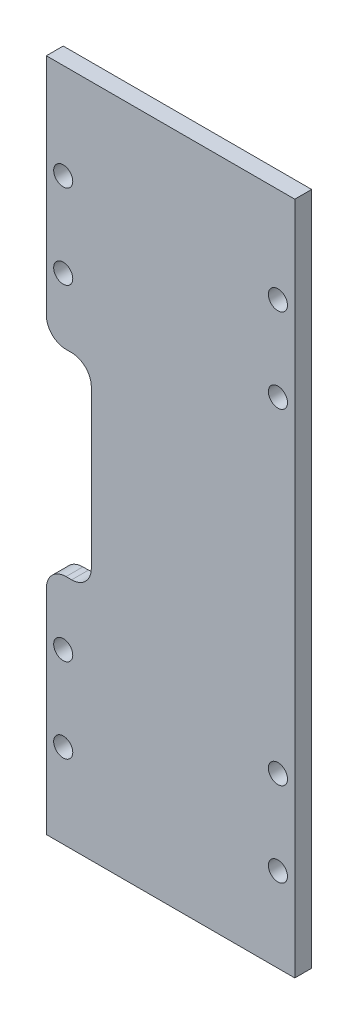
SolidWorks part; units mm, degrees
material "6061-T6 (SS)"
ref_plane "Front Plane" through (0, 0, 0) normal (0, 0, 1) x (1, 0, 0)
ref_plane "Top Plane" through (0, 0, 0) normal (0, 1, 0) x (1, 0, 0)
ref_plane "Right Plane" through (0, 0, 0) normal (1, 0, 0) x (0, 0, -1)
sketch "d" plane through (0, 0, 0) normal (0, 0, 1) x (1, 0, 0)
  line L1 (-21.7876, 70.4698) -> (22.4124, 70.4698)
  line L2 (-21.7876, 70.4698) -> (-21.7876, -49.5302)
  line L3 (-21.7876, -49.5302) -> (22.4124, -49.5302)
  line L4 (22.4124, 70.4698) -> (22.4124, -49.5302)
  dimension "D1" = 44.2
  dimension "D2" = 120
extrude "Boss-Extrude1" add sketch "d" along normal blind 3
sketch "Sketch4" plane through (0, 0, 3) normal (0, 0, 1) x (1, 0, 0)
  line L0 (0.3124, -49.5302) -> (0.3124, 98.4185) construction
  line L1 (-21.7876, -49.5302) -> (22.4124, -49.5302) construction
  point P0 (-18.7876, 53.4698)
  point P3 (-18.7876, 38.4698)
  point P6 (-18.7876, -19.5302)
  point P9 (-18.7876, -34.5302)
  point P20 (19.4124, -34.5302)
  point P21 (19.4124, -19.5302)
  point P22 (19.4124, 38.4698)
  point P23 (19.4124, 53.4698)
hole_wizard "M3 Clearance Hole1" positions "Sketch4" profile "Sketch5" hole size "M3" standard "DIN"
sketch "Sketch5" plane through (-18.7876, 53.4698, 3) normal (1, 0, 0) x (0, -1, 0)
  line L0 (0, 0) -> (0, 16.0215)
  line L1 (0, 16.0215) -> (1.7, 15)
  line L2 (1.7, 15) -> (1.7, 0)
  line L5 (1.7, 0) -> (0, 0)
  line L10 (0, 16.0215) -> (-1.7, 15) construction
  line L11 (0, -6.35) -> (0, 107.95) construction
  dimension "Hole Dia." = 3.4
  dimension "Hole Depth" = 15
  dimension "Drill Angle" = 118
sketch "Sketch6" plane through (0, 0, 3) normal (0, 0, 1) x (1, 0, 0)
  line L5 (-21.7876, 70.4698) -> (-21.7876, -49.5302) construction
  line L6 (-21.7876, 26.9698) -> (-13.7876, 26.9698)
  line L7 (-21.7876, 26.9698) -> (-21.7876, -8.0302)
  line L8 (-21.7876, -8.0302) -> (-13.7876, -8.0302)
  line L9 (-13.7876, 26.9698) -> (-13.7876, -8.0302)
  line L10 (22.4124, 70.4698) -> (-21.7876, 70.4698) construction
  dimension "D1" = 35
  dimension "D2" = 8
  dimension "D3" = 43.5
extrude "Cut-Extrude1" cut sketch "Sketch6" against normal through all
fillet "Fillet1" radius 3.5 4 edges at (-21.7876, -8.0302, 1.5) (-13.7876, -8.0302, 1.5) (-21.7876, 26.9698, 1.5) (-13.7876, 26.9698, 1.5)
